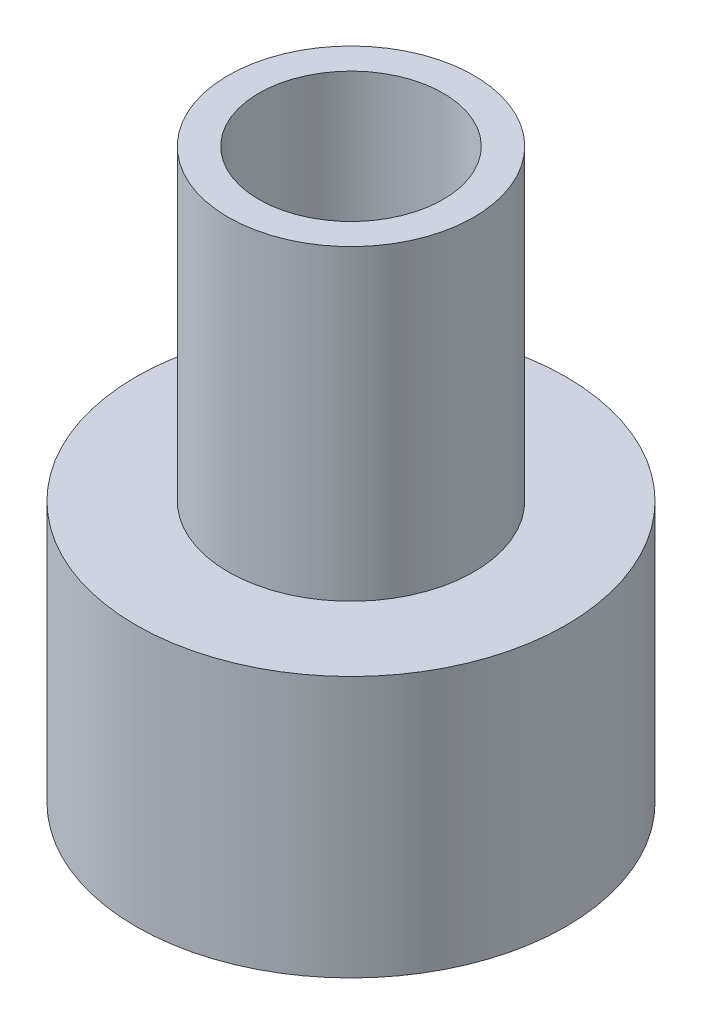
SolidWorks part; units mm, degrees
ref_plane "Front Plane" through (0, 0, 0) normal (0, 0, 1) x (1, 0, 0)
ref_plane "Top Plane" through (0, 0, 0) normal (0, 1, 0) x (1, 0, 0)
ref_plane "Right Plane" through (0, 0, 0) normal (1, 0, 0) x (0, 0, -1)
sketch "Sketch1" plane through (0, 0, 0) normal (0, 1, 0) x (1, 0, 0)
  circle A0 centre (0, 0) radius 4
  circle A1 centre (0, 0) radius 3
  dimension "D1" = 8
  dimension "D2" = 6
extrude "Boss-Extrude1" add sketch "Sketch1" along normal blind 10
sketch "Sketch2" plane through (0, 0, 0) normal (0, 1, 0) x (1, 0, 0)
  circle A0 centre (0, 0) radius 7
  dimension "D1" = 14
extrude "Boss-Extrude2" add sketch "Sketch2" against normal blind 8.5
sketch "Sketch3" plane through (0, -8.5, 0) normal (0, -1, 0) x (1, 0, 0)
  circle A0 centre (0, 0) radius 6
  dimension "D1" = 12
extrude "Cut-Extrude1" cut sketch "Sketch3" against normal offset from surface (6.5 mm away) 2 up to face at (0, 0, 4)
